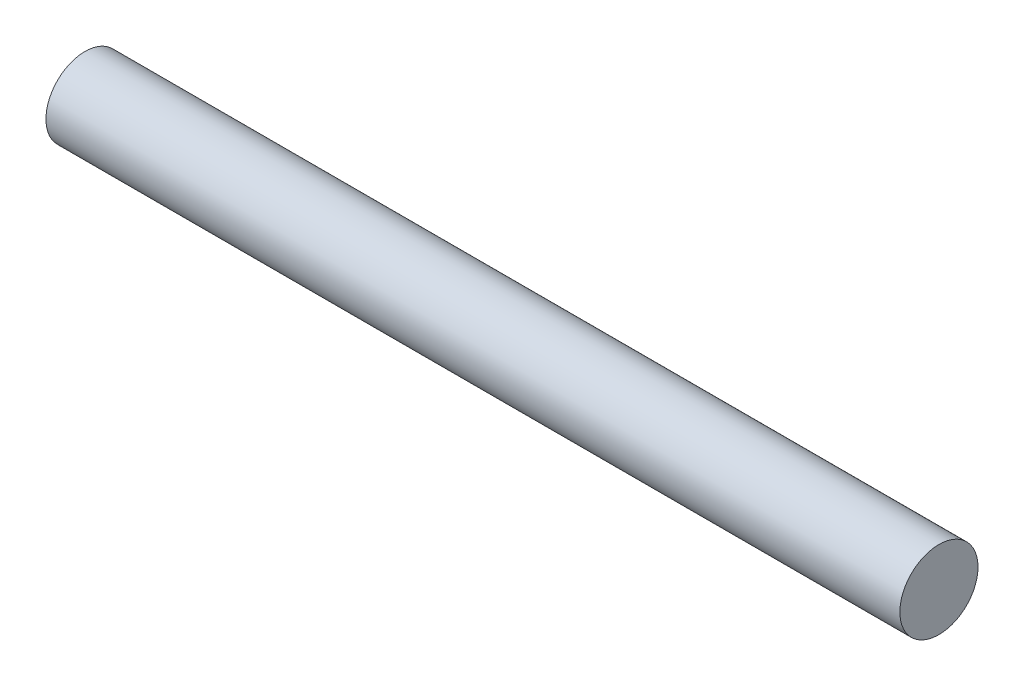
SolidWorks part; units mm, degrees
ref_plane "Frontal" through (0, 0, 0) normal (0, 0, 1) x (1, 0, 0)
ref_plane "Superior" through (0, 0, 0) normal (0, 1, 0) x (1, 0, 0)
ref_plane "Lateral" through (0, 0, 0) normal (1, 0, 0) x (0, 0, -1)
sketch "Sketch2" plane through (0, 0, 0) normal (1, 0, 0) x (0, 0, -1)
  circle A0 centre (0, 0) radius 3.5
  dimension "D1" = 7
extrude "Base-Extrude" add sketch "Sketch2" along normal blind 76.5
